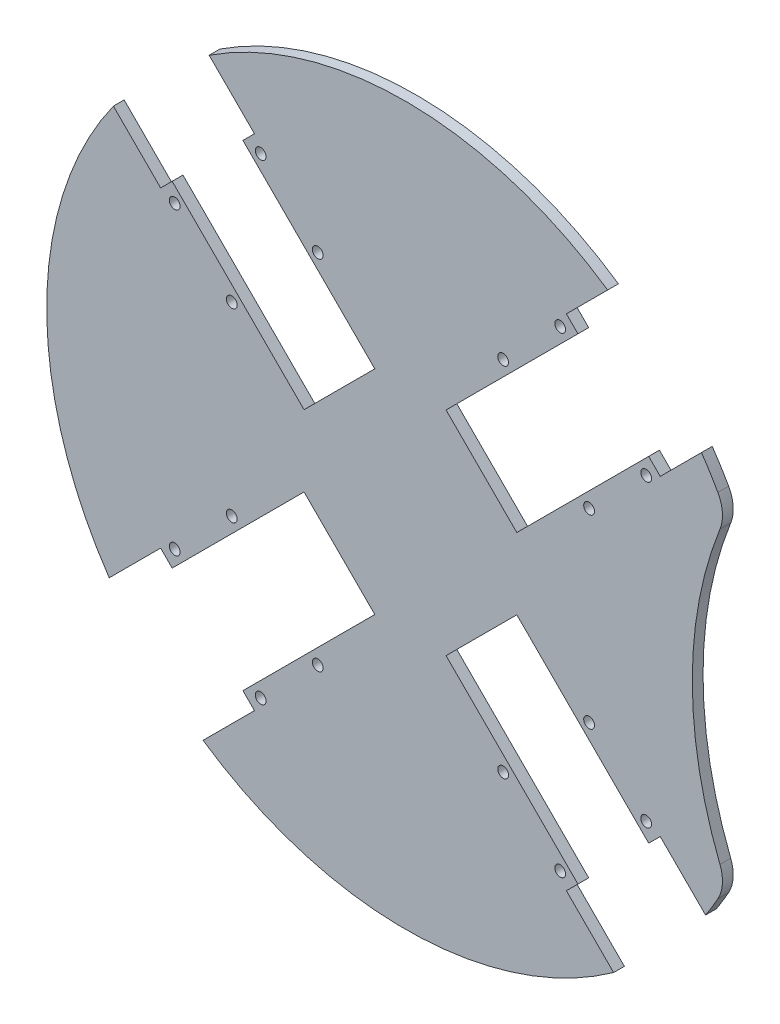
SolidWorks part; units mm, degrees
ref_plane "Alzado" through (0, 0, 0) normal (0, 0, 1) x (1, 0, 0)
ref_plane "Planta" through (0, 0, 0) normal (0, 1, 0) x (1, 0, 0)
ref_plane "Vista lateral" through (0, 0, 0) normal (1, 0, 0) x (0, 0, -1)
sketch "Croquis1" plane through (0, 0, 0) normal (0, 0, 1) x (1, 0, 0)
  circle A0 centre (0, 0) radius 100
  dimension "D1" = 200
extrude "Saliente-Extruir1" add sketch "Croquis1" along normal blind 3
sketch "Croquis3" plane through (0, 0, 3) normal (0, 0, 1) x (1, 0, 0)
  line L0 (0, 0) -> (190, 0) construction
  circle A0 centre (190, 0) radius 110
  dimension "D1" = 220
  dimension "D2" = 190
extrude "Cortar-Extruir1" cut sketch "Croquis3" against normal blind 3
fillet "Redondeo1" radius 10 2 edges at (89.4737, -44.6594, 1.5) (89.4737, 44.6594, 1.5)
sketch "Croquis4" plane through (0, 0, 3) normal (0, 0, 1) x (1, 0, 0)
  line L0 (0, 0) -> (-70.7107, -70.7107) construction
  line L1 (-83.7922, -57.6292) -> (-57.6292, -83.7922)
  line L2 (-57.6292, -83.7922) -> (-42.0729, -68.2358)
  line L3 (-83.7922, -57.6292) -> (-68.2358, -42.0729)
  line L4 (-65.0185, -45.2902) -> (-28.2489, -8.5206)
  line L5 (-68.2358, -42.0729) -> (-65.0185, -45.2902)
  line L6 (-45.2902, -65.0185) -> (-42.0729, -68.2358)
  line L7 (-28.2489, -8.5206) -> (-8.5206, -28.2489)
  line L8 (-8.5206, -28.2489) -> (-45.2902, -65.0185)
  line L9 (0, 0) -> (0, -100) construction
  line L10 (0, 0) -> (-100, 0) construction
  line L11 (-8.5206, 31.0773) -> (-28.2489, 11.3491)
  line L12 (-45.2902, 67.8469) -> (-8.5206, 31.0773)
  line L13 (-28.2489, 11.3491) -> (-65.0185, 48.1186)
  line L14 (-65.0185, 48.1186) -> (-68.2358, 44.9013)
  line L15 (-83.7922, 60.4576) -> (-68.2358, 44.9013)
  line L16 (-57.6292, 86.6206) -> (-83.7922, 60.4576)
  line L17 (-57.6292, 86.6206) -> (-42.0729, 71.0642)
  line L18 (-42.0729, 71.0642) -> (-45.2902, 67.8469)
  line L19 (31.0773, 11.3491) -> (11.3491, 31.0773)
  line L20 (67.8469, 48.1186) -> (31.0773, 11.3491)
  line L21 (11.3491, 31.0773) -> (48.1186, 67.8469)
  line L22 (48.1186, 67.8469) -> (44.9013, 71.0642)
  line L23 (60.4576, 86.6206) -> (44.9013, 71.0642)
  line L24 (86.6206, 60.4576) -> (60.4576, 86.6206)
  line L25 (86.6206, 60.4576) -> (71.0642, 44.9013)
  line L26 (71.0642, 44.9013) -> (67.8469, 48.1186)
  line L27 (11.3491, -28.2489) -> (31.0773, -8.5206)
  line L28 (48.1186, -65.0185) -> (11.3491, -28.2489)
  line L29 (31.0773, -8.5206) -> (67.8469, -45.2902)
  line L30 (67.8469, -45.2902) -> (71.0642, -42.0729)
  line L31 (86.6206, -57.6292) -> (71.0642, -42.0729)
  line L32 (60.4576, -83.7922) -> (86.6206, -57.6292)
  line L33 (60.4576, -83.7922) -> (44.9013, -68.2358)
  line L34 (44.9013, -68.2358) -> (48.1186, -65.0185)
  arc A0 (87.1345, 49.0671) -> (87.1345, -49.0671) centre (0, 0) ccw construction
  point P43 (1.4142, 1.4142)
  dimension "D2" = 22
  dimension "D3" = 22
  dimension "D4" = 27.9
  dimension "D5" = 37
  dimension "D6" = 4.55
  dimension "D7" = 100
  dimension "D8" = 52
  dimension "D9" = 52
  dimension "D10" = 45
  dimension "D11" = 4.55
  dimension "D12" = 4
  dimension "D13" = 13.95
  dimension "D14" = 26
extrude "Cortar-Extruir2" cut sketch "Croquis4" against normal through all
sketch "Croquis5" plane through (0, 0, 3) normal (0, 0, 1) x (1, 0, 0)
  line L0 (-65.0185, -45.2902) -> (-62.19, -42.4618) construction
  line L1 (-28.2489, -8.5206) -> (-65.0185, -45.2902) construction
  line L2 (-62.19, -42.4618) -> (-64.3114, -40.3404) construction
  line L3 (-64.3114, -40.3404) -> (-48.4015, -24.4305) construction
  line L4 (-65.0185, -45.2902) -> (-68.2358, -42.0729) construction
  line L5 (-18.3848, -18.3848) -> (-65.0185, -65.0185) construction
  line L6 (-8.5206, -28.2489) -> (-28.2489, -8.5206) construction
  line L7 (-42.0729, -68.2358) -> (-45.2902, -65.0185) construction
  line L8 (-42.4618, -62.19) -> (-40.3404, -64.3114) construction
  line L9 (-45.2902, -65.0185) -> (-42.4618, -62.19) construction
  line L10 (11.3491, -28.2489) -> (48.1186, -65.0185) construction
  line L11 (-65.0185, 48.1186) -> (-28.2489, 11.3491) construction
  line L12 (-8.5206, 31.0773) -> (-45.2902, 67.8469) construction
  line L13 (48.1186, 67.8469) -> (11.3491, 31.0773) construction
  line L14 (31.0773, 11.3491) -> (67.8469, 48.1186) construction
  line L15 (67.8469, -45.2902) -> (31.0773, -8.5206) construction
  line L16 (-68.2358, 44.9013) -> (-65.0185, 48.1186) construction
  line L17 (-45.2902, 67.8469) -> (-42.0729, 71.0642) construction
  line L18 (44.9013, 71.0642) -> (48.1186, 67.8469) construction
  line L19 (67.8469, 48.1186) -> (71.0642, 44.9013) construction
  line L20 (71.0642, -42.0729) -> (67.8469, -45.2902) construction
  line L21 (48.1186, -65.0185) -> (44.9013, -68.2358) construction
  circle A0 centre (-64.3114, -40.3404) radius 1.5
  circle A1 centre (-48.4015, -24.4305) radius 1.5
  circle A2 centre (-24.4305, -48.4015) radius 1.5
  circle A3 centre (-40.3404, -64.3114) radius 1.5
  circle A4 centre (-24.4305, 51.2299) radius 1.5
  circle A5 centre (-40.3404, 67.1398) radius 1.5
  circle A6 centre (-48.4015, 27.259) radius 1.5
  circle A7 centre (-64.3114, 43.1689) radius 1.5
  circle A8 centre (51.2299, 27.259) radius 1.5
  circle A9 centre (67.1398, 43.1689) radius 1.5
  circle A10 centre (27.259, 51.2299) radius 1.5
  circle A11 centre (43.1689, 67.1398) radius 1.5
  circle A12 centre (27.259, -48.4015) radius 1.5
  circle A13 centre (43.1689, -64.3114) radius 1.5
  circle A14 centre (51.2299, -24.4305) radius 1.5
  circle A15 centre (67.1398, -40.3404) radius 1.5
  point P50 (0, 0)
  dimension "D1" = 3
  dimension "D2" = 3
  dimension "D3" = 3
  dimension "D4" = 3
  dimension "D5" = 4
  dimension "D6" = 26.5
  dimension "D7" = 4
  dimension "D8" = 3
  dimension "D9" = 3
  dimension "D10" = 3
  dimension "D11" = 3
  dimension "D12" = 3
  dimension "D13" = 3
  dimension "D14" = 3
  dimension "D15" = 3
  dimension "D16" = 3
  dimension "D17" = 3
  dimension "D18" = 3
  dimension "D19" = 3
  dimension "D20" = 3
  dimension "D21" = 3
  dimension "D22" = 3
  dimension "D23" = 3
  dimension "D24" = 3
  dimension "D25" = 3
  dimension "D26" = 3
  dimension "D27" = 3
  dimension "D28" = 3
  dimension "D29" = 3
  dimension "D30" = 3
  dimension "D31" = 3
  dimension "D32" = 3
  dimension "D33" = 22.5
  dimension "D34" = 22.5
  dimension "D35" = 22.5
  dimension "D36" = 22.5
  dimension "D37" = 22.5
  dimension "D38" = 22.5
  dimension "D39" = 4
  dimension "D40" = 4
  dimension "D42" = 4
  dimension "D43" = 4
  dimension "D44" = 4
  dimension "D41" = 4
extrude "Cortar-Extruir3" cut sketch "Croquis5" against normal blind 10
